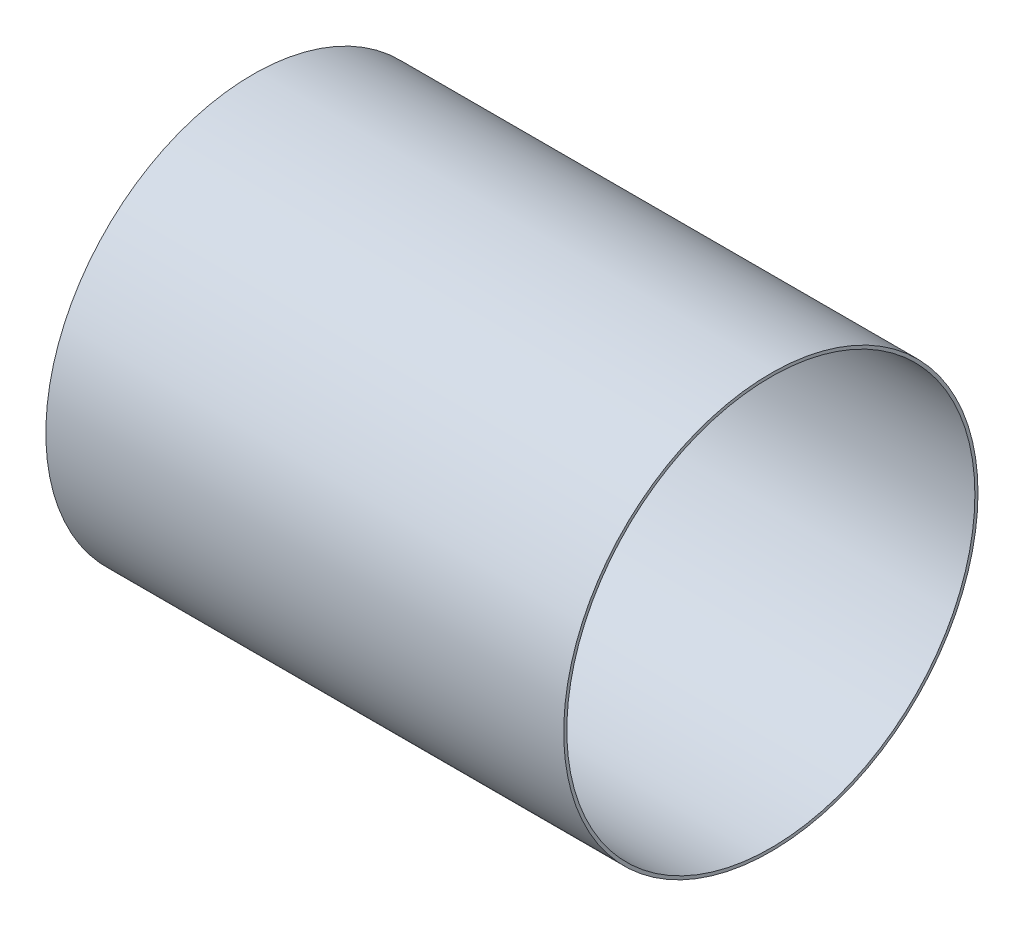
SolidWorks part; units mm, degrees
material "AISI 304"
ref_plane "Front Plane" through (0, 0, 0) normal (0, 0, 1) x (1, 0, 0)
ref_plane "Top Plane" through (0, 0, 0) normal (0, 1, 0) x (1, 0, 0)
ref_plane "Right Plane" through (0, 0, 0) normal (1, 0, 0) x (0, 0, -1)
sketch "Sketch1" plane through (0, 0, 0) normal (1, 0, 0) x (0, 0, -1)
  circle A0 centre (0, 0) radius 200
  circle A1 centre (0, 0) radius 197
  dimension "D1" = 400
  dimension "D2" = 3
extrude "Boss-Extrude1" add sketch "Sketch1" along normal blind 500
sketch "Sketch2" plane through (0, 0, 0) normal (1, 0, 0) x (0, 0, -1)
  circle A0 centre (0, 0) radius 200
ref_plane "Plane1" through (-180, 0, 0) normal (1, 0, 0) x (0, 0, -1)
